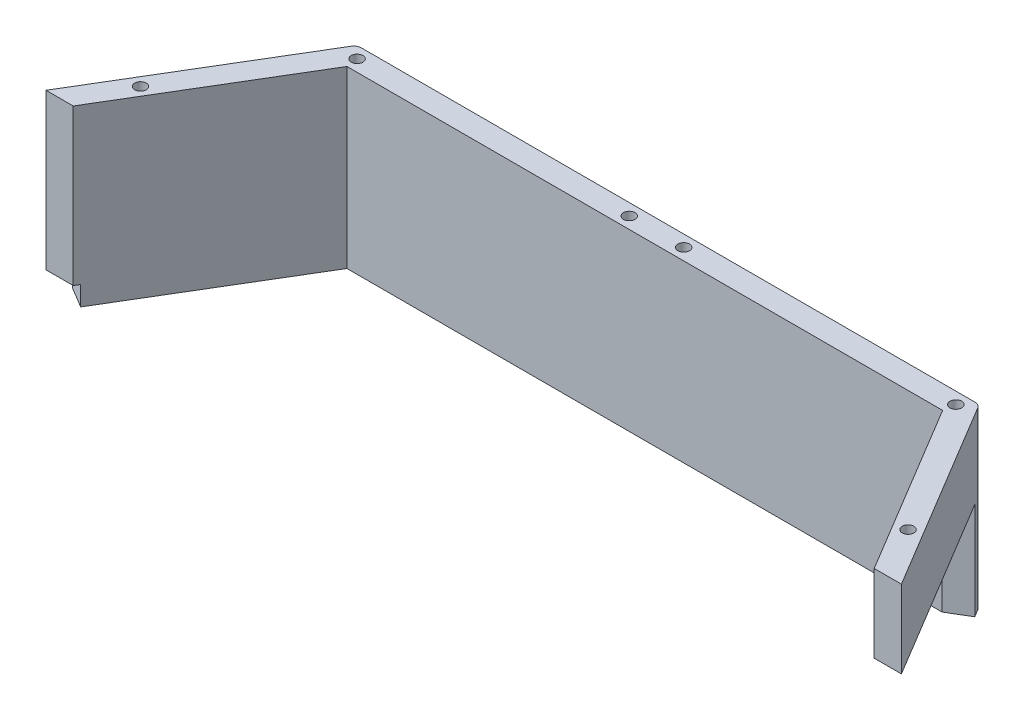
SolidWorks part; units mm, degrees
ref_plane "Front Plane" through (0, 0, 0) normal (0, 0, 1) x (1, 0, 0)
ref_plane "Top Plane" through (0, 0, 0) normal (0, 1, 0) x (1, 0, 0)
ref_plane "Right Plane" through (0, 0, 0) normal (1, 0, 0) x (0, 0, -1)
sketch "Sketch1" plane through (0, 0, 0) normal (0, 1, 0) x (1, 0, 0)
  line L0 (-110, 0) -> (-80, 50)
  line L1 (-80, 50) -> (80, 50)
  line L3 (76.6, 44) -> (-76.6, 44)
  line L4 (-76.6, 44) -> (-103, 0)
  line L5 (-103, 0) -> (-110, 0)
  line L6 (0, -55) -> (0, 55) construction
  line L7 (103, 0) -> (110, 0)
  line L8 (76.6, 44) -> (103, 0)
  line L9 (110, 0) -> (80, 50)
  dimension "D1" = 6
  dimension "D2" = 7
  dimension "D3" = 50
  dimension "D4" = 30
extrude "Boss-Extrude1" add sketch "Sketch1" along normal mid plane 45
sketch "Sketch2" plane through (0, 22.5, 0) normal (0, 1, 0) x (1, 0, 0)
  line L1 (-80, 50) -> (-110, 0) construction
  line L2 (80, 50) -> (-80, 50) construction
  line L3 (0, -55) -> (0, 55) construction
  circle A0 centre (-98.7014, 13) radius 1.5
  circle A1 centre (-77, 47) radius 1.5
  circle A2 centre (-7, 47) radius 1.5
  circle A3 centre (7, 47) radius 1.5
  circle A4 centre (77, 47) radius 1.5
  circle A5 centre (98.7014, 13) radius 1.5
  dimension "D2" = 3
  dimension "D3" = 3
  dimension "D5" = 3
  dimension "D1" = 70
  dimension "D4" = 7
  dimension "D6" = 3
  dimension "D7" = 3
  dimension "D8" = 3
  dimension "D9" = 37
extrude "Cut-Extrude1" cut sketch "Sketch2" against normal blind 5
fillet "Fillet1" radius 2 2 edges at (80, 0, -50) (-80, 0, -50)
sketch "Sketch4" plane through (80.8824, 0, -48.5294) normal (0.8575, 0, -0.5145) x (-0.5145, 0, -0.8575)
  line L0 (-56.5945, 22.5) -> (-56.5945, -22.5) construction
  line L1 (-56.5945, 2.5) -> (-1.5945, 2.5)
  line L2 (-56.5945, 2.5) -> (-56.5945, -22.5)
  line L3 (-56.5945, -22.5) -> (-1.5945, -22.5)
  line L4 (-1.5945, 2.5) -> (-1.5945, -22.5)
  line L5 (-56.5945, 22.5) -> (0.5826, 22.5) construction
  dimension "D1" = 55
  dimension "D2" = 25
  dimension "D3" = 20
extrude "Cut-Extrude3" cut sketch "Sketch4" against normal blind 10
sketch "Sketch5" plane through (-75.7353, 0, -45.4412) normal (0.8575, 0, 0.5145) x (0.5145, 0, -0.8575)
  line L0 (-56.5945, 22.5) -> (-56.5945, -22.5) construction
  line L1 (-56.5945, -17.5) -> (-51.5945, -17.5)
  line L2 (-56.5945, -17.5) -> (-56.5945, -22.5)
  line L3 (-56.5945, -22.5) -> (-51.5945, -22.5)
  line L4 (-51.5945, -17.5) -> (-51.5945, -22.5)
  line L5 (-52.9931, -22.5) -> (-1.6807, -22.5) construction
  dimension "D1" = 5
  dimension "D2" = 5
extrude "Cut-Extrude4" cut sketch "Sketch5" against normal blind 10
